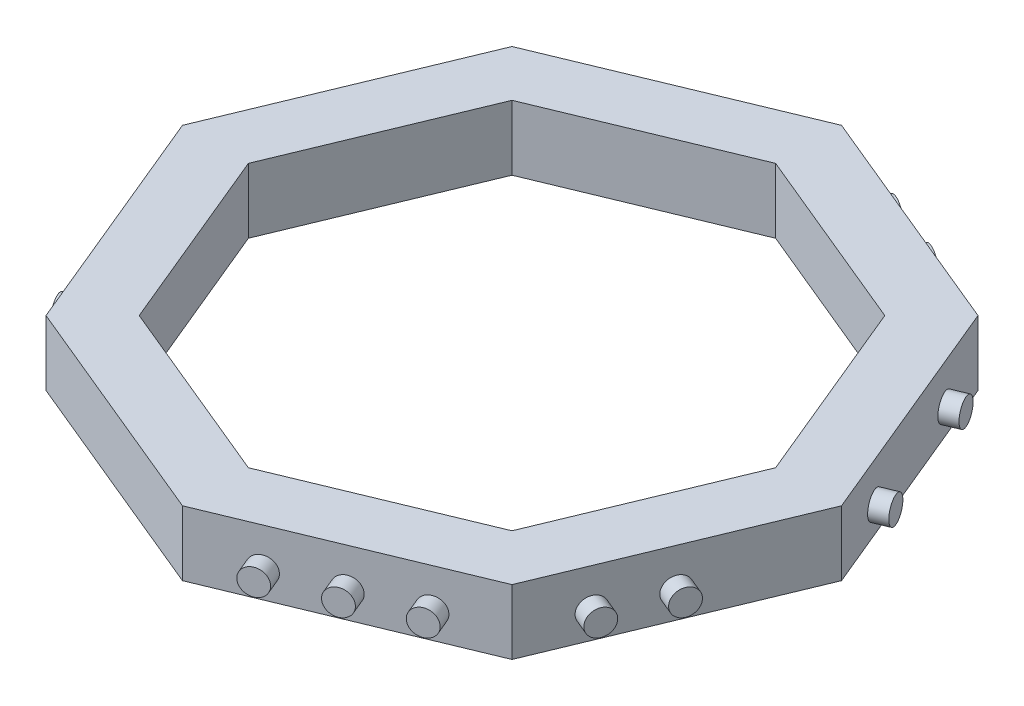
SolidWorks part; units mm, degrees
ref_plane "Front Plane" through (0, 0, 0) normal (0, 0, 1) x (1, 0, 0)
ref_plane "Top Plane" through (0, 0, 0) normal (0, 1, 0) x (1, 0, 0)
ref_plane "Right Plane" through (0, 0, 0) normal (1, 0, 0) x (0, 0, -1)
sketch "Sketch3" plane through (0, 0, 0) normal (0, 1, 0) x (1, 0, 0)
  line L1 (25.4, 0) -> (17.9605, 17.9605)
  line L2 (17.9605, 17.9605) -> (0, 25.4)
  line L3 (0, 25.4) -> (-17.9605, 17.9605)
  line L4 (-17.9605, 17.9605) -> (-25.4, 0)
  line L5 (-25.4, 0) -> (-17.9605, -17.9605)
  line L6 (-17.9605, -17.9605) -> (0, -25.4)
  line L7 (0, -25.4) -> (17.9605, -17.9605)
  line L8 (17.9605, -17.9605) -> (25.4, 0)
  circle A0 centre (0, 0) radius 23.4665 construction
  dimension "D1" = 25.4
extrude "Boss-Extrude1" add sketch "Sketch3" along normal blind 5
sketch "Sketch5" plane through (0, 5, 0) normal (0, 1, 0) x (1, 0, 0)
  line L1 (20.32, 0) -> (14.3684, 14.3684)
  line L2 (14.3684, 14.3684) -> (0, 20.32)
  line L3 (0, 20.32) -> (-14.3684, 14.3684)
  line L4 (-14.3684, 14.3684) -> (-20.32, 0)
  line L5 (-20.32, 0) -> (-14.3684, -14.3684)
  line L6 (-14.3684, -14.3684) -> (0, -20.32)
  line L7 (0, -20.32) -> (14.3684, -14.3684)
  line L8 (14.3684, -14.3684) -> (20.32, 0)
  circle A0 centre (0, 0) radius 18.7732 construction
  dimension "D1" = 20.32
extrude "Cut-Extrude1" cut sketch "Sketch5" against normal blind 5
sketch "Sketch6" plane through (8.9803, 0, 21.6803) normal (0.3827, 0, 0.9239) x (0.9239, 0, -0.3827)
  circle A0 centre (0, 2) radius 1
  circle A1 centre (-5, 2) radius 1
  circle A2 centre (5, 2) radius 1
sketch "Sketch7" plane through (-21.6803, 0, 8.9803) normal (-0.9239, 0, 0.3827) x (0.3827, 0, 0.9239)
  circle A0 centre (5, 2) radius 1
sketch "Sketch8" plane through (-21.6803, 0, -8.9803) normal (-0.9239, 0, -0.3827) x (-0.3827, 0, 0.9239)
  circle A0 centre (0, 2) radius 1
sketch "Sketch9" plane through (-8.9803, 0, -21.6803) normal (-0.3827, 0, -0.9239) x (-0.9239, 0, 0.3827)
  circle A0 centre (-5, 2) radius 1
sketch "Sketch10" plane through (8.9803, 0, -21.6803) normal (0.3827, 0, -0.9239) x (-0.9239, 0, -0.3827)
  circle A0 centre (0, 2) radius 1
  circle A1 centre (5, 2) radius 1
sketch "Sketch11" plane through (21.6803, 0, -8.9803) normal (0.9239, 0, -0.3827) x (-0.3827, 0, -0.9239)
  circle A0 centre (5, 2) radius 1
  circle A1 centre (-5, 2) radius 1
sketch "Sketch12" plane through (21.6803, 0, 8.9803) normal (0.9239, 0, 0.3827) x (0.3827, 0, -0.9239)
  circle A0 centre (0, 2) radius 1
  circle A1 centre (-5, 2) radius 1
extrude "Boss-Extrude5" add sketch "Sketch6" along normal blind 1.25 contours A2 | A1 | A0
extrude "Boss-Extrude6" add sketch "Sketch7" along normal blind 1.25 contours A0
extrude "Boss-Extrude7" add sketch "Sketch8" along normal blind 1.25 contours A0
extrude "Boss-Extrude8" add sketch "Sketch9" along normal blind 1.25 contours A0
extrude "Boss-Extrude9" add sketch "Sketch10" along normal blind 1.25 contours A0 | A1
extrude "Boss-Extrude10" add sketch "Sketch11" along normal blind 1.25 contours A1 | A0
extrude "Boss-Extrude11" add sketch "Sketch12" along normal blind 1.25 contours A1 | A0
